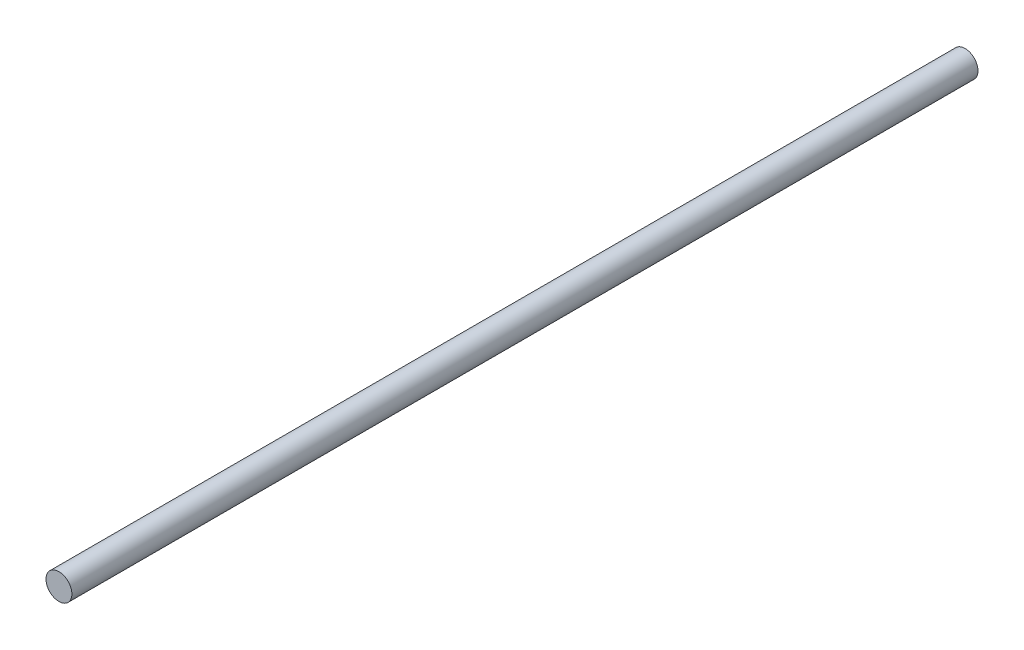
SolidWorks part; units mm, degrees
material "201 Annealed Stainless Steel (SS)"
ref_plane "Front Plane" through (0, 0, 0) normal (0, 0, 1) x (1, 0, 0)
ref_plane "Top Plane" through (0, 0, 0) normal (0, 1, 0) x (1, 0, 0)
ref_plane "Right Plane" through (0, 0, 0) normal (1, 0, 0) x (0, 0, -1)
sketch "Sketch1" plane through (0, 0, 0) normal (0, 0, 1) x (1, 0, 0)
  circle A0 centre (0, 0) radius 1
  dimension "D1" = 2
extrude "Boss-Extrude1" add sketch "Sketch1" along normal blind 70
